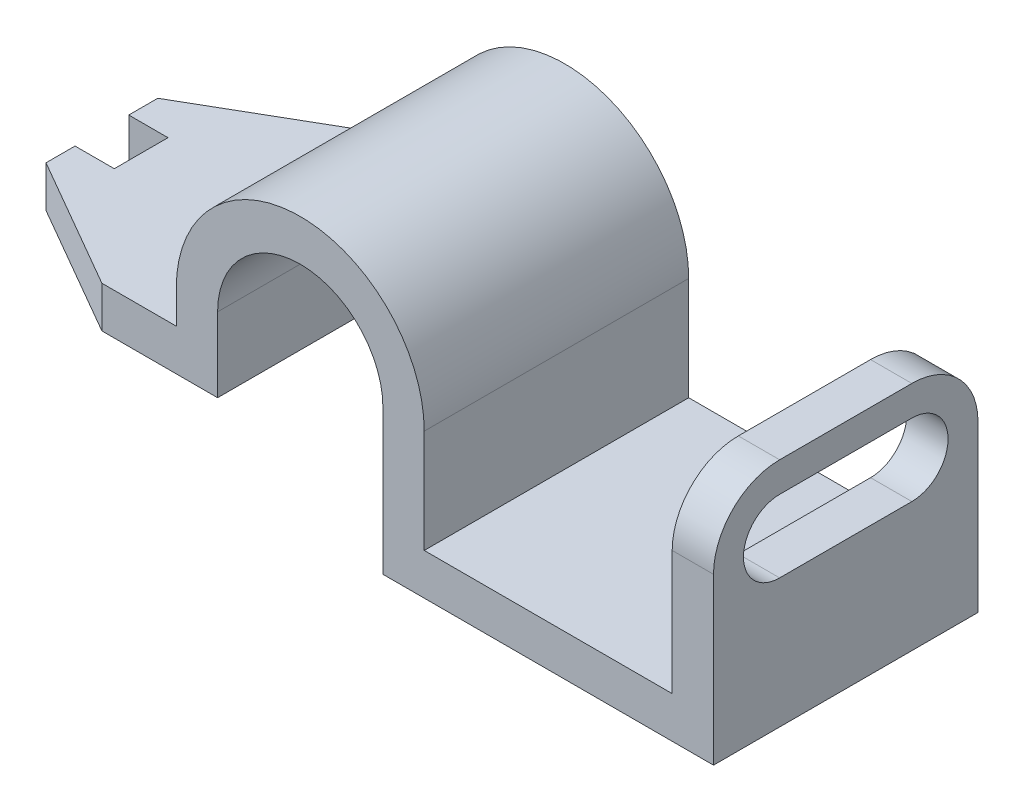
SolidWorks part; units mm, degrees
ref_plane "Alzado" through (0, 0, 0) normal (0, 0, 1) x (1, 0, 0)
ref_plane "Planta" through (0, 0, 0) normal (0, 1, 0) x (1, 0, 0)
ref_plane "Vista lateral" through (0, 0, 0) normal (1, 0, 0) x (0, 0, -1)
sketch "Croquis1" plane through (0, 0, 0) normal (0, 0, 1) x (1, 0, 0)
  line L0 (-100, 27) -> (-100, 17)
  line L1 (-100, 17) -> (-40, 17)
  line L2 (-40, 17) -> (-40, 35)
  line L3 (-100, 27) -> (-50, 27)
  line L4 (-50, 27) -> (-50, 35)
  line L5 (0, 35) -> (0, 0)
  line L6 (0, 0) -> (80, 0)
  line L7 (80, 0) -> (80, 56)
  line L8 (80, 56) -> (70, 56)
  line L9 (70, 56) -> (70, 10)
  line L10 (70, 10) -> (10, 10)
  line L11 (10, 10) -> (10, 35)
  arc A0 (-50, 35) -> (10, 35) centre (-20, 35) cw
  arc A1 (-40, 35) -> (0, 35) centre (-20, 35) cw
  point P2 (0, 0)
  point P9 (28.7462, 16.0019)
  point P18 (0, 12.5512)
  point P19 (0, 0)
  point P20 (22.6731, 20.8776)
  point P21 (34.4959, 7.3456)
  point P22 (0, 0)
  point P23 (40, 4.7229)
  point P24 (49.3423, 20.9598)
  point P25 (49.3782, 9.6134)
  point P26 (0, 0)
  point P27 (0, 0)
  point P28 (20, 37.9062)
  point P29 (0, 0)
  point P30 (0, 0)
  point P31 (0, 0)
  point P32 (50, 75.1176)
  point P33 (20, 61.0481)
  point P34 (50, -17)
  point P35 (0, 0)
  point P36 (0, 0)
  dimension "D1" = 20
  dimension "D2" = 30
  dimension "D3" = 10
  dimension "D4" = 10
  dimension "D5" = 56
  dimension "D6" = 35
  dimension "D7" = 10
  dimension "D8" = 18
  dimension "D9" = 60
  dimension "D10" = 80
extrude "Saliente-Extruir1" add sketch "Croquis1" along normal mid plane 64
sketch "Croquis2" plane through (0, 27, 0) normal (0, 1, 0) x (1, 0, 0)
  line L0 (-100, 13.5248) -> (-68, 32)
  line L1 (-100, -32) -> (-100, 32) construction
  line L2 (-50, 32) -> (-100, 32) construction
  line L3 (-100, 0) -> (80, 0) construction
  line L4 (80, -32) -> (80, 32) construction
  line L5 (-100, 13.5248) -> (-100, 32)
  line L6 (-100, 6.5) -> (-90.5, 6.5)
  line L7 (-100, 6.5) -> (-100, -6.5)
  line L8 (-100, -6.5) -> (-90.5, -6.5)
  line L9 (-90.5, 6.5) -> (-90.5, -6.5)
  line L10 (-100, 32) -> (-68, 32)
  line L11 (-100, -13.5248) -> (-100, -32)
  line L12 (-100, -13.5248) -> (-68, -32)
  line L13 (-100, -32) -> (-68, -32)
  point P14 (-100, 0)
  dimension "D1" = 30
  dimension "D2" = 32
  dimension "D3" = 13
  dimension "D4" = 9.5
extrude "Cortar-Extruir1" cut sketch "Croquis2" against normal up to next
sketch "Croquis4" plane through (80, 0, 0) normal (1, 0, 0) x (0, 0, -1)
  line L0 (-16, 40) -> (16, 40) construction
  line L1 (-16, 48.75) -> (16, 48.75)
  line L2 (-16, 31.25) -> (16, 31.25)
  line L3 (-32, 0) -> (32, 0) construction
  arc A0 (-16, 48.75) -> (-16, 31.25) centre (-16, 40) ccw
  arc A1 (16, 31.25) -> (16, 48.75) centre (16, 40) ccw
  point P2 (0, 40)
  point P7 (0, 0)
  dimension "D1" = 17.5
  dimension "D2" = 32
  dimension "D3" = 40
extrude "Cortar-Extruir2" cut sketch "Croquis4" against normal up to next
fillet "Redondeo2" radius 16 2 edges at (75, 56, -32) (75, 56, 32)
